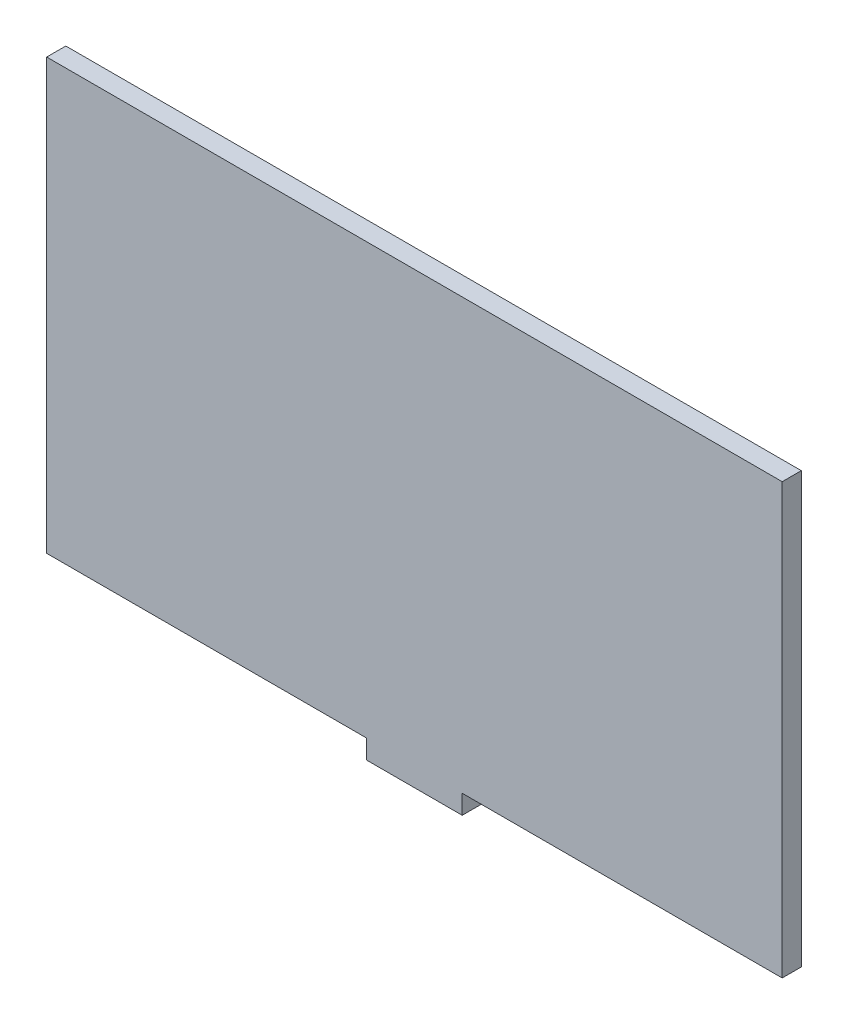
SolidWorks part; units mm, degrees
ref_plane "前视基准面" through (0, 0, 0) normal (0, 0, 1) x (1, 0, 0)
ref_plane "上视基准面" through (0, 0, 0) normal (0, 1, 0) x (1, 0, 0)
ref_plane "右视基准面" through (0, 0, 0) normal (1, 0, 0) x (0, 0, -1)
sketch "草图2" plane through (0, 0, 0) normal (0, 0, 1) x (1, 0, 0)
  line L0 (9.4465, -32.6987) -> (42.9465, -32.6987)
  line L1 (-34.0535, 12.3013) -> (42.9465, 12.3013)
  line L2 (-34.0535, 12.3013) -> (-34.0535, -32.6987)
  line L3 (-34.0535, -32.6987) -> (-0.5535, -32.6987)
  line L4 (42.9465, 12.3013) -> (42.9465, -32.6987)
  line L5 (-0.5535, -34.6987) -> (9.4465, -34.6987)
  line L6 (-0.5535, -34.6987) -> (-0.5535, -32.6987)
  line L8 (9.4465, -34.6987) -> (9.4465, -32.6987)
  line L9 (-0.5535, -34.6987) -> (9.4465, -32.6987) construction
  line L10 (-0.5535, -32.6987) -> (9.4465, -34.6987) construction
  point P4 (4.4465, -33.6987)
  point P9 (4.4465, 12.3013)
  dimension "D1" = 77
  dimension "D2" = 2
  dimension "45" = 45
  dimension "D3" = 10
extrude "凸台-拉伸1" add sketch "草图2" along normal blind 2
